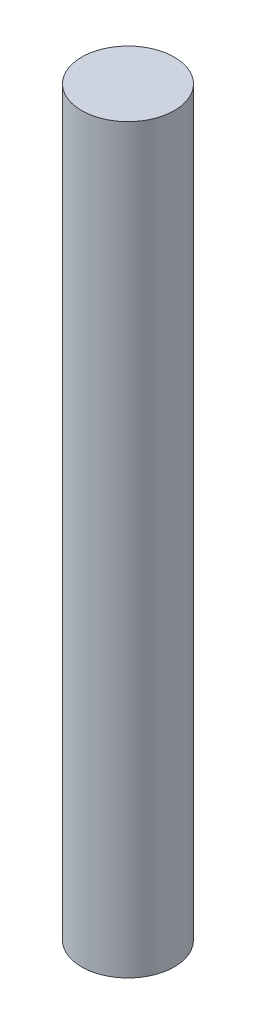
SolidWorks part; units mm, degrees
ref_plane "前视基准面" through (0, 0, 0) normal (0, 0, 1) x (1, 0, 0)
ref_plane "上视基准面" through (0, 0, 0) normal (0, 1, 0) x (1, 0, 0)
ref_plane "右视基准面" through (0, 0, 0) normal (1, 0, 0) x (0, 0, -1)
sketch "草图1" plane through (0, 0, 0) normal (0, 1, 0) x (1, 0, 0)
  circle A0 centre (0, 0) radius 1
extrude "凸台-拉伸1" add sketch "草图1" along normal blind 16
